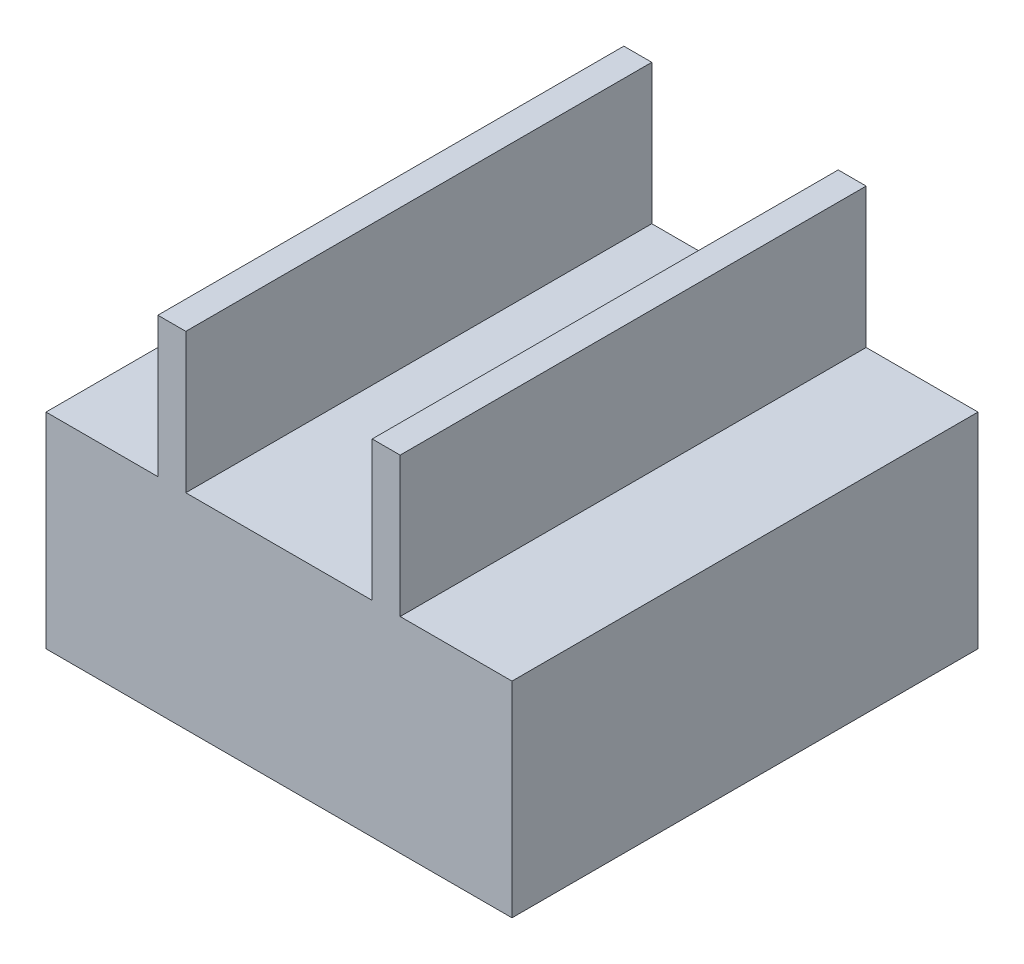
SolidWorks part; units mm, degrees
ref_plane "前视基准面" through (0, 0, 0) normal (0, 0, 1) x (1, 0, 0)
ref_plane "上视基准面" through (0, 0, 0) normal (0, 1, 0) x (1, 0, 0)
ref_plane "右视基准面" through (0, 0, 0) normal (1, 0, 0) x (0, 0, -1)
sketch "草图1" plane through (0, 0, 0) normal (0, 1, 0) x (1, 0, 0)
  line L1 (25, 25) -> (-25, 25)
  line L2 (25, 25) -> (25, -25)
  line L3 (25, -25) -> (-25, -25)
  line L4 (-25, 25) -> (-25, -25)
  line L5 (25, 25) -> (-25, -25) construction
  line L6 (25, -25) -> (-25, 25) construction
  point P0 (0, 0)
  dimension "D1" = 50
  dimension "D2" = 50
extrude "凸台-拉伸1" add sketch "草图1" along normal blind 2
sketch "草图2" plane through (0, 2, 0) normal (0, 1, 0) x (1, 0, 0)
  line L0 (0, 25) -> (0, -25) construction
  line L1 (25, 25) -> (-25, 25) construction
  line L2 (-25, -25) -> (25, -25) construction
  line L3 (10, 25) -> (10, -25)
  line L4 (-10, 25) -> (-10, -25)
  line L6 (-13, 25) -> (13, 25)
  line L7 (-13, 25) -> (-13, -25)
  line L8 (-13, -25) -> (13, -25)
  line L9 (13, 25) -> (13, -25)
  line M2 (-25, -25) -> (25, -25)
  line M4 (25, 25) -> (-25, 25)
  dimension "D3" = 3
  dimension "D4" = 3
  dimension "D1" = 10
  dimension "D2" = 10
extrude "凸台-拉伸2" add sketch "草图2" along normal blind 15 contours L7 L4 M4 M2 | L9 L3 M4 M2
ref_plane "基准面4" through (0, 10.8253, -18.75) normal (0, 0.5, -0.866) x (-1, 0, 0)
sketch "草图5" plane through (0, 0, 0) normal (1, 0, 0) x (0, 0, -1)
  line L0 (-25, 0) -> (-36.547, -20)
  line L1 (-36.547, -20) -> (36.547, -20)
  line L2 (0, -20) -> (0, 0)
  line L3 (25, 0) -> (-25, 0)
  line L4 (0, 0) -> (0, -35.7659) construction
  line L5 (25, 0) -> (36.547, -20)
  dimension "D1" = 120
  dimension "D2" = 20
extrude "凸台-拉伸3" add sketch "草图5" along normal blind 25 and the other way blind 25 contours L5 L3 L2 L1 | L2 L3 L0 L1
sketch "草图6" plane through (0, 0, 0) normal (0, 0, 1) x (1, 0, 0)
  line L0 (-25, 0) -> (-36.547, -20)
  line L1 (-36.547, -20) -> (-25, -20)
  line L2 (0, 0) -> (0, -28.6433) construction
  line L3 (-25, 0) -> (25, 0) construction
  line L4 (-25, 0) -> (-25, -20) construction
  line L5 (-25, -20) -> (-25, 0)
  dimension "D1" = 150
extrude "凸台-拉伸4" add sketch "草图6" along normal up to surface and the other way up to surface up to face at (0, -10, 30.7735) other way up to face at (0, -10, -30.7735)
mirror "镜向1" about plane through (0, 0, 0) normal (1, 0, 0) of "凸台-拉伸4"
sketch "草图7" plane through (0, 2, 0) normal (0, 1, 0) x (1, 0, 0)
  line L1 (-25, 25) -> (25, 25)
  line L2 (-25, 25) -> (-25, -25)
  line L3 (-25, -25) -> (25, -25)
  line L4 (25, 25) -> (25, -25)
  line L5 (-40.235, 41.874) -> (53.5164, 41.874)
  line L6 (-40.235, 41.874) -> (-40.235, -45.9328)
  line L7 (-40.235, -45.9328) -> (53.5164, -45.9328)
  line L8 (53.5164, 41.874) -> (53.5164, -45.9328)
extrude "切除-拉伸1" cut sketch "草图7" against normal blind 25
sketch "草图8" plane through (0, -20, 0) normal (0, -1, 0) x (1, 0, 0)
  line L1 (22, -22) -> (-22, -22)
  line L2 (22, -22) -> (22, 22)
  line L3 (22, 22) -> (-22, 22)
  line L4 (-22, -22) -> (-22, 22)
  line L5 (22, -22) -> (-22, 22) construction
  line L6 (22, 22) -> (-22, -22) construction
  point P0 (0, 0)
  dimension "D1" = 44
  dimension "D2" = 44
extrude "切除-拉伸2" cut sketch "草图8" against normal blind 18
chamfer "倒角1" distance 2 angle 45 4 edges at (22, -20, 0) (0, -20, -22) (0, -20, 22) (-22, -20, 0)
